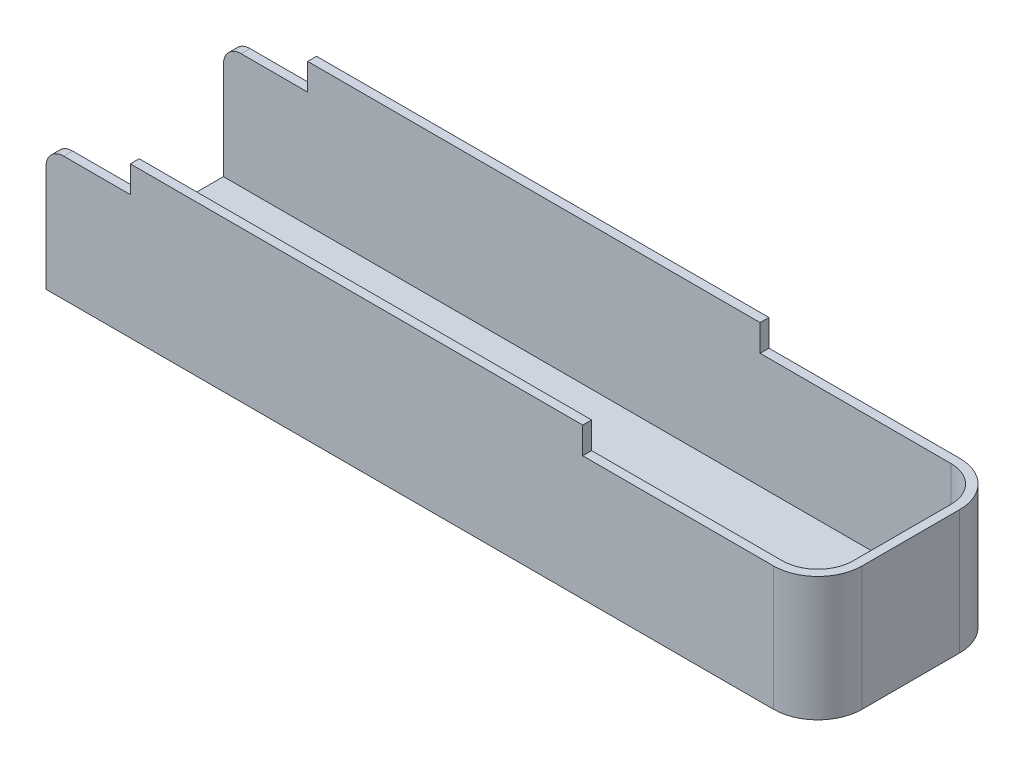
SolidWorks part; units mm, degrees
ref_plane "Спереди" through (0, 0, 0) normal (0, 0, 1) x (1, 0, 0)
ref_plane "Сверху" through (0, 0, 0) normal (0, 1, 0) x (1, 0, 0)
ref_plane "Справа" through (0, 0, 0) normal (1, 0, 0) x (0, 0, -1)
sketch "Эскиз1" plane through (0, 0, 0) normal (0, 1, 0) x (1, 0, 0)
  line L0 (-42.5, -1003.0422) -> (-42.5, 48996.9578) construction
  line L1 (42.5, -1010.7137) -> (42.5, 48989.2863) construction
  line L2 (0, -1000) -> (0, 49000) construction
  line L3 (-1000, 0) -> (49000, 0) construction
  line L4 (-1071.9102, 9.5) -> (48928.0898, 9.5) construction
  line L5 (-1058.7891, -9.5) -> (48941.2109, -9.5) construction
  line L6 (-42.5, 9.5) -> (-42.5, -9.5)
  line L7 (-42.5, -9.5) -> (38.5, -9.5)
  line L8 (42.5, -5.5) -> (42.5, 5.5)
  line L9 (38.5, 9.5) -> (-42.5, 9.5)
  line L10 (38.5, 10.5) -> (-43.5, 10.5)
  line L11 (-43.5, 10.5) -> (-43.5, -10.5)
  line L12 (-43.5, -10.5) -> (38.5, -10.5)
  line L13 (43.5, -5.5) -> (43.5, 5.5)
  arc A0 (38.5, -9.5) -> (42.5, -5.5) centre (38.5, -5.5) ccw
  arc A1 (42.5, 5.5) -> (38.5, 9.5) centre (38.5, 5.5) ccw
  arc A2 (38.5, -10.5) -> (43.5, -5.5) centre (38.5, -5.5) ccw
  arc A3 (43.5, 5.5) -> (38.5, 10.5) centre (38.5, 5.5) ccw
  point P19 (42.5, -9.5)
  point P22 (42.5, 9.5)
extrude "Бобышка-Вытянуть1" add sketch "Эскиз1" along normal blind 17
sketch "Эскиз2" plane through (0, 0, 0) normal (0, -1, 0) x (1, 0, 0)
  line L1 (-43.5, 10.5) -> (-43.5, -10.5)
  line L3 (-43.5, -10.5) -> (38.5, -10.5)
  line L4 (-43.5, 10.5) -> (38.5, 10.5)
  line L5 (43.5, 5.5) -> (43.5, -5.5)
  arc A0 (38.5, 10.5) -> (43.5, 5.5) centre (38.5, 5.5) cw
  arc A1 (43.5, -5.5) -> (38.5, -10.5) centre (38.5, -5.5) cw
extrude "Бобышка-Вытянуть2" add sketch "Эскиз2" against normal blind 1
sketch "Эскиз3" plane through (0, 17, 0) normal (0, 1, 0) x (1, 0, 0)
  line L0 (-38.5689, 9.5) -> (-51.652, 9.5)
  line L1 (38.5, 9.5) -> (-42.5, 9.5) construction
  line L2 (-38.5689, 9.5) -> (-38.5689, -9.5)
  line L3 (-42.5, -9.5) -> (38.5, -9.5) construction
  line L4 (-38.5689, -9.5) -> (-51.652, -9.5)
  line L5 (-51.652, -9.5) -> (-51.652, 9.5)
extrude "Вырез-Вытянуть1" cut sketch "Эскиз3" against normal blind 16
sketch "Эскиз4" plane through (0, 0, 10.5) normal (0, 0, 1) x (1, 0, 0)
  line L0 (43.5, -983) -> (43.5, 49017) construction
  line L1 (17, -987.6567) -> (17, 49012.3433) construction
  line L2 (-956.5, 17) -> (49043.5, 17) construction
  line L3 (-966.0399, 14) -> (49033.9601, 14) construction
  line L4 (17, 17) -> (43.5, 17)
  line L5 (43.5, 17) -> (43.5, 14)
  line L6 (43.5, 14) -> (17, 14)
  line L7 (17, 14) -> (17, 17)
extrude "Вырез-Вытянуть2" cut sketch "Эскиз4" against normal blind 26
sketch "Эскиз5" plane through (0, 0, 10.5) normal (0, 0, 1) x (1, 0, 0)
  line L0 (-43.5, -983) -> (-43.5, 49017) construction
  line L1 (-34, -987.2441) -> (-34, 49012.7559) construction
  line L2 (-1043.5, 17) -> (48956.5, 17) construction
  line L3 (-956.5, 14) -> (49043.5, 14) construction
  line L4 (-43.5, 17) -> (-34, 17)
  line L5 (-34, 17) -> (-34, 14)
  line L6 (-34, 14) -> (-43.5, 14)
  line L7 (-43.5, 14) -> (-43.5, 17)
extrude "Вырез-Вытянуть3" cut sketch "Эскиз5" against normal blind 26
fillet "Скругление1" radius 2 2 edges at (-43.5, 14, -10) (-43.5, 14, 10)
